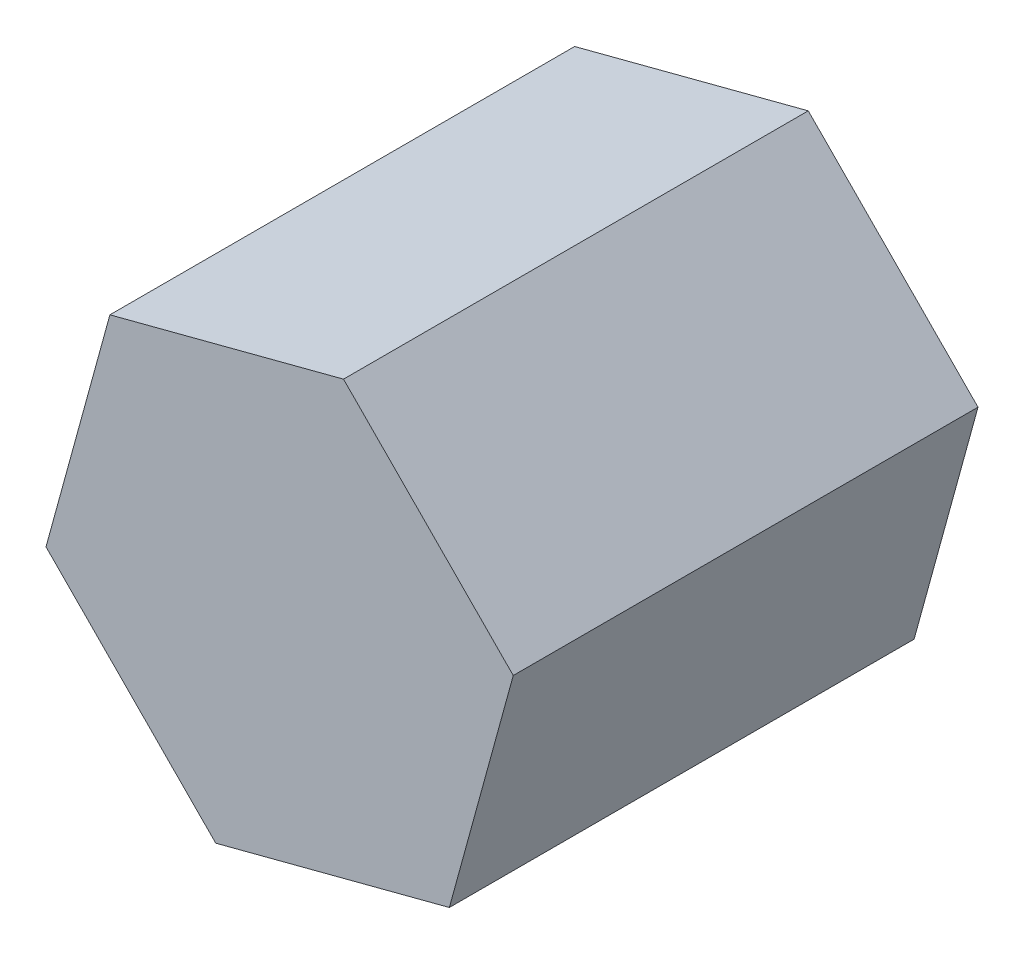
SolidWorks part; units mm, degrees
material "Brass"
ref_plane "Front Plane" through (0, 0, 0) normal (0, 0, 1) x (1, 0, 0)
ref_plane "Top Plane" through (0, 0, 0) normal (0, 1, 0) x (1, 0, 0)
ref_plane "Right Plane" through (0, 0, 0) normal (1, 0, 0) x (0, 0, -1)
sketch "Sketch1" plane through (0, 0, 0) normal (0, 0, 1) x (1, 0, 0)
  line L1 (104.6577, -30.5115) -> (101.6414, -31.3004)
  line L2 (101.6414, -31.3004) -> (100.8165, -34.307)
  line L3 (100.8165, -34.307) -> (103.0078, -36.5247)
  line L4 (103.0078, -36.5247) -> (106.024, -35.7358)
  line L5 (106.024, -35.7358) -> (106.849, -32.7292)
  line L6 (106.849, -32.7292) -> (104.6577, -30.5115)
  circle A0 centre (103.8327, -33.5181) radius 2.7 construction
extrude "Boss-Extrude1" add sketch "Sketch1" along normal blind 6
